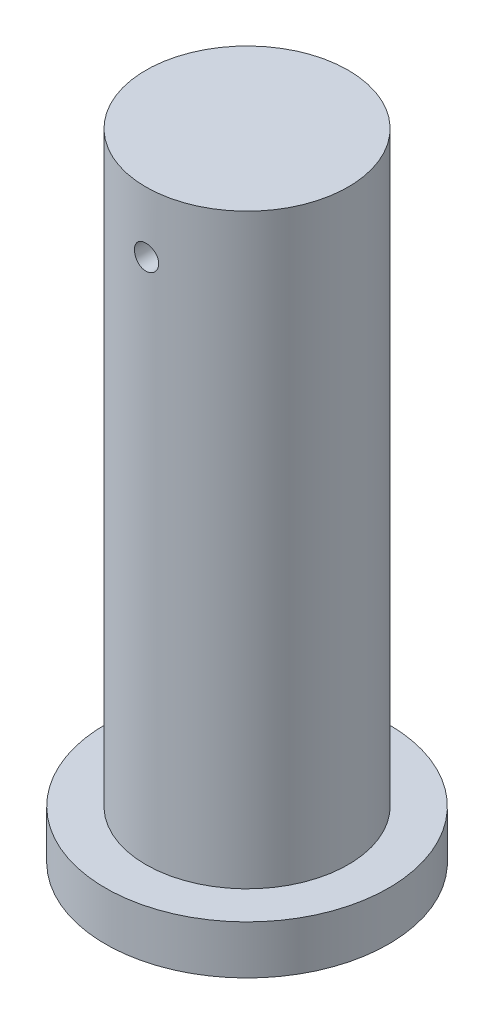
SolidWorks part; units mm, degrees
ref_plane "Front Plane" through (0, 0, 0) normal (1, 0, 0) x (0, 1, 0)
ref_plane "Top Plane" through (0, 0, 0) normal (0, 0, 1) x (0, 1, 0)
ref_plane "Right Plane" through (0, 0, 0) normal (0, 1, 0) x (-1, 0, 0)
sketch "Sketch1" plane through (0, 0, 0) normal (1, 0, 0) x (0, 1, 0)
  line L0 (0, 0) -> (0, 25)
  line L1 (0, 25) -> (-145, 25)
  line L2 (-145, 25) -> (-145, 35)
  line L3 (-145, 35) -> (-157, 35)
  line L4 (-157, 35) -> (-157, 0)
  line L5 (-157, 0) -> (0, 0)
  dimension "D1" = 25
  dimension "D2" = 12
  dimension "D3" = 157
  dimension "D4" = 35
revolve "Revolve1" add sketch "Sketch1" angle 360 about L5
sketch "Sketch2" plane through (0, 0, 0) normal (0, 0, 1) x (0, 1, 0)
  line L0 (-145, -35) -> (-145, 35) construction
  circle A0 centre (-15, 0) radius 3
  point P4 (0, 0)
  point P6 (0, 0)
  dimension "D1" = 6
  dimension "D2" = 130
extrude "Cut-Extrude1" cut sketch "Sketch2" against normal through all both and the other way through all
